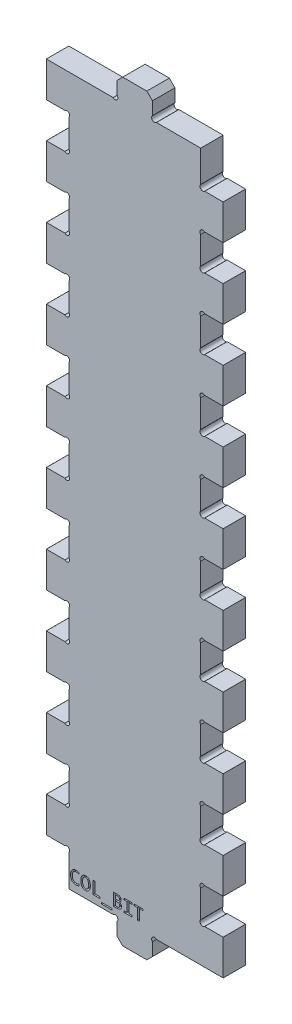
SolidWorks part; units mm, degrees
material "PVC Rigid"
ref_plane "Front Plane" through (0, 0, 0) normal (0, 0, 1) x (1, 0, 0)
ref_plane "Top Plane" through (0, 0, 0) normal (0, 1, 0) x (1, 0, 0)
ref_plane "Right Plane" through (0, 0, 0) normal (1, 0, 0) x (0, 0, -1)
sketch "Model" [suppressed]
  dimension "D3" = 0.7937
  dimension "D1" = 10
  dimension "D2" = 10
sketch "Sketch1" plane through (0, 0, 0) normal (0, 0, 1) x (1, 0, 0)
  line L1 (0, 0) -> (50, 0)
  line L2 (0, 0) -> (0, 200.0001)
  line L3 (0, 200.0001) -> (50, 200.0001)
  line L4 (50, 0) -> (50, 200.0001)
  dimension "D1" = 200.0001
  dimension "D2" = 50
extrude "Boss-Extrude1" add sketch "Sketch1" along normal blind 6.35
sketch "Sketch2" plane through (0, 0, 0) normal (0, 0, 1) x (1, 0, 0)
  line L0 (0, 100.0001) -> (50, 100.0001) construction
  line L1 (50, 200.0001) -> (0, 200.0001) construction
  line L2 (25, 200.0001) -> (25, 203.1751) construction
  line L3 (20, 206.3501) -> (30, 206.3501)
  line L4 (20, 206.3501) -> (20, 200.0001)
  line L5 (20, 200.0001) -> (30, 200.0001)
  line L6 (30, 206.3501) -> (30, 200.0001)
  line L7 (20, 206.3501) -> (30, 200.0001) construction
  line L8 (20, 200.0001) -> (30, 206.3501) construction
  line L9 (0, 200.0001) -> (0, 0) construction
  line L10 (50, 0) -> (50, 200.0001) construction
  line L11 (20, 0) -> (30, -6.35) construction
  line L12 (20, -6.35) -> (30, 0) construction
  line L13 (25, 0) -> (25, -3.175) construction
  line L14 (30, -6.35) -> (30, 0)
  line L15 (20, 0) -> (30, 0)
  line L16 (20, -6.35) -> (20, 0)
  line L17 (20, -6.35) -> (30, -6.35)
  dimension "D1" = 6.35
  dimension "D2" = 10
extrude "Boss-Extrude2" add sketch "Sketch2" along normal blind 6.35
sketch "Sketch3" plane through (0, 0, 6.35) normal (0, 0, 1) x (1, 0, 0)
  line L0 (25, 206.3501) -> (25, -6.35) construction
  line L1 (30, 206.3501) -> (20, 206.3501) construction
  line L2 (20, -6.35) -> (30, -6.35) construction
  line L3 (6.35, 200.0001) -> (6.35, 0) construction
  line L4 (20, 200.0001) -> (0, 200.0001) construction
  line L5 (0, 0) -> (20, 0) construction
  line L6 (0, 200.0001) -> (0, 0) construction
  line L7 (6.35, 0) -> (0, 0)
  line L8 (6.35, 0) -> (6.35, 10)
  line L9 (6.35, 10) -> (0, 10)
  line L10 (0, 0) -> (0, 10)
  line L11 (50, 0) -> (50, 10)
  line L12 (43.65, 10) -> (50, 10)
  line L13 (43.65, 0) -> (43.65, 10)
  line L14 (43.65, 0) -> (50, 0)
  dimension "D1" = 6.35
  dimension "D2" = 10
extrude "Cut-Extrude1" [suppressed] cut sketch "Sketch3" against normal blind 6.35
pattern_linear "LPattern2" [suppressed] count 10 spacing 20
sketch "Sketch4" [suppressed] plane through (0, 0, 6.35) normal (0, 0, 1) x (1, 0, 0)
  line L0 (0, 10) -> (6.35, 0) construction
  line L1 (6.35, 10) -> (5.2275, 10) construction
  line L2 (0.5613, 0.5613) -> (5.7887, 0.5613) construction
  line L3 (0.5613, 0.5613) -> (0.5613, 9.4387) construction
  line L4 (0.5613, 9.4387) -> (5.7887, 9.4387) construction
  line L5 (5.7887, 0.5613) -> (5.7887, 9.4387) construction
  line L6 (0.5613, 0.5613) -> (5.7887, 9.4387) construction
  line L7 (0.5613, 9.4387) -> (5.7887, 0.5613) construction
  line L8 (6.35, 10) -> (0, 10) construction
  line L9 (6.35, 10) -> (6.35, 8.8775) construction
  line L10 (6.35, 0) -> (6.35, 10) construction
  line L11 (25, 206.3501) -> (25, -6.35) construction
  line L12 (30, 206.3501) -> (20, 206.3501) construction
  line L13 (20, -6.35) -> (30, -6.35) construction
  line L14 (44.2113, 9.4387) -> (44.2113, 20.5613) construction
  line L15 (43.65, 10) -> (43.65, 8.8775) construction
  line L16 (49.4387, 9.4387) -> (44.2113, 0.5613) construction
  line L17 (49.4387, 0.5613) -> (44.2113, 9.4387) construction
  line L18 (44.2113, 0.5613) -> (44.2113, 9.4387) construction
  line L19 (49.4387, 9.4387) -> (44.2113, 9.4387) construction
  line L20 (49.4387, 0.5613) -> (49.4387, 9.4387) construction
  line L21 (49.4387, 0.5613) -> (44.2113, 0.5613) construction
  line L22 (43.65, 10) -> (44.7725, 10) construction
  line L23 (5.7887, 9.4387) -> (5.7887, 20.5613) construction
  line L24 (50, 10) -> (43.65, 0) construction
  circle A0 centre (5.7887, 9.4387) radius 0.7938
  circle A4 centre (5.7887, 20.5613) radius 0.7938
  circle A7 centre (44.2113, 20.5613) radius 0.7937
  circle A8 centre (44.2113, 9.4387) radius 0.7937
  point P4 (3.175, 5)
  point P40 (46.825, 5)
  dimension "D1" = 1.5875
extrude "Cut-Extrude3" [suppressed] cut sketch "Sketch4" against normal blind 6.35
pattern_linear "LPattern3" [suppressed] count 9 spacing 20
sketch "Sketch8" plane through (0, 0, 6.35) normal (0, 0, 1) x (1, 0, 0)
  line L0 (6.35, 200.0001) -> (6.35, 0) construction
  line L1 (20, 200.0001) -> (0, 200.0001) construction
  line L2 (0, 0) -> (20, 0) construction
  line L3 (0, 200.0001) -> (0, 0) construction
  line L4 (43.65, 200.0001) -> (43.65, 0) construction
  line L5 (0, 0) -> (6.35, 0)
  line L6 (0, 0) -> (0, 10)
  line L7 (0, 10) -> (6.35, 10)
  line L8 (6.35, 0) -> (6.35, 10)
  line L9 (50, 200.0001) -> (30, 200.0001) construction
  line L10 (30, 0) -> (50, 0) construction
  line L11 (50, 0) -> (50, 200.0001) construction
  line L12 (43.65, 10) -> (50, 10)
  line L13 (43.65, 10) -> (43.65, 20)
  line L14 (43.65, 20) -> (50, 20)
  line L15 (50, 10) -> (50, 20)
  dimension "D1" = 6.35
  dimension "D2" = 10
  dimension "D3" = 10
  dimension "D4" = 6.35
  dimension "D5" = 10
extrude "Cut-Extrude6" cut sketch "Sketch8" against normal through all
pattern_linear "LPattern4" count 10 spacing 20 along (0, 1, 0) of "Cut-Extrude6"
sketch "Sketch9" plane through (0, 0, 6.35) normal (0, 0, 1) x (1, 0, 0)
  line L0 (0, 30) -> (6.35, 20) construction
  line L1 (6.35, 30) -> (5.2275, 30) construction
  line L2 (0.5613, 20.5613) -> (5.7887, 20.5613) construction
  line L3 (0.5613, 20.5613) -> (0.5613, 29.4388) construction
  line L4 (0.5613, 29.4388) -> (5.7887, 29.4388) construction
  line L5 (5.7887, 20.5613) -> (5.7887, 29.4388) construction
  line L6 (0.5613, 20.5613) -> (5.7887, 29.4388) construction
  line L7 (0.5613, 29.4388) -> (5.7887, 20.5613) construction
  line L8 (6.35, 30) -> (0, 30) construction
  line L9 (6.35, 30) -> (6.35, 28.8775) construction
  line L10 (6.35, 20) -> (6.35, 30) construction
  line L11 (43.65, 20) -> (50, 10) construction
  line L12 (43.65, 20) -> (44.7725, 20) construction
  line L13 (44.2113, 10.5613) -> (49.4387, 10.5613) construction
  line L14 (44.2113, 10.5613) -> (44.2113, 19.4387) construction
  line L15 (44.2113, 19.4387) -> (49.4387, 19.4387) construction
  line L16 (49.4387, 10.5613) -> (49.4387, 19.4387) construction
  line L17 (44.2113, 10.5613) -> (49.4387, 19.4387) construction
  line L18 (44.2113, 19.4387) -> (49.4387, 10.5613) construction
  line L19 (50, 20) -> (43.65, 20) construction
  line L20 (43.65, 20) -> (43.65, 18.8775) construction
  line L21 (43.65, 20) -> (43.65, 10) construction
  line L22 (50, 20) -> (50, 30) construction
  circle A0 centre (5.7887, 29.4388) radius 0.7938
  circle A1 centre (5.7887, 20.5613) radius 0.7938
  circle A2 centre (44.2113, 19.4387) radius 0.7937
  circle A3 centre (44.2113, 10.5613) radius 0.7937
  point P4 (3.175, 25)
  point P23 (46.825, 15)
  dimension "D1" = 1.5875
  dimension "D2" = 10
extrude "Cut-Extrude7" cut sketch "Sketch9" against normal through all
pattern_linear "LPattern5" count 9 spacing 20 along (0, 1, 0) of "Cut-Extrude7"
sketch "Sketch10" plane through (0, 0, 6.35) normal (0, 0, 1) x (1, 0, 0)
  line L0 (0, 10) -> (6.35, 0) construction
  line L1 (5.2275, 10) -> (6.35, 10) construction
  line L2 (0.5613, 0.5613) -> (5.7887, 0.5613) construction
  line L3 (0.5613, 0.5613) -> (0.5613, 9.4387) construction
  line L4 (0.5613, 9.4387) -> (5.7887, 9.4387) construction
  line L5 (5.7887, 0.5613) -> (5.7887, 9.4387) construction
  line L6 (0.5613, 0.5613) -> (5.7887, 9.4387) construction
  line L7 (0.5613, 9.4387) -> (5.7887, 0.5613) construction
  line L8 (6.35, 10) -> (0, 10) construction
  line L9 (6.35, 10) -> (6.35, 8.8775) construction
  line L10 (6.35, 0) -> (6.35, 10) construction
  line L11 (6.35, 5) -> (3.175, 5) construction
  line L12 (0, 200.0001) -> (50, 0) construction
  line L13 (43.65, 200.0001) -> (50, 190.0001) construction
  line L14 (44.7725, 190.0001) -> (43.65, 190.0001) construction
  line L15 (44.2113, 190.5614) -> (49.4387, 190.5614) construction
  line L16 (44.2113, 190.5614) -> (44.2113, 199.4388) construction
  line L17 (44.2113, 199.4388) -> (49.4387, 199.4388) construction
  line L18 (49.4387, 190.5614) -> (49.4387, 199.4388) construction
  line L19 (44.2113, 190.5614) -> (49.4387, 199.4388) construction
  line L20 (44.2113, 199.4388) -> (49.4387, 190.5614) construction
  line L21 (43.65, 190.0001) -> (50, 190.0001) construction
  line L22 (43.65, 190.0001) -> (43.65, 191.1226) construction
  line L23 (43.65, 200.0001) -> (43.65, 190.0001) construction
  circle A0 centre (5.7887, 9.4387) radius 0.7938
  circle A2 centre (44.2113, 190.5614) radius 0.7937
  point P4 (3.175, 5)
  point P28 (46.825, 195.0001)
  dimension "D1" = 1.5875
  dimension "D2" = 1.5875
extrude "Cut-Extrude8" cut sketch "Sketch10" against normal through all
chamfer "Chamfer1" distance 1.5875 angle 45 4 edges at (30, -6.35, 3.175) (20, -6.35, 3.175) (20, 206.3501, 3.175) (30, 206.3501, 3.175)
sketch "Sketch5" [suppressed] plane through (0, 0, 6.35) normal (0, 0, 1) x (1, 0, 0)
  line L0 (6.35, 180.0001) -> (0, 190.0001) construction
  line L1 (6.35, 190.0001) -> (5.2275, 190.0001) construction
  line L2 (0.5613, 180.5614) -> (5.7887, 180.5614) construction
  line L3 (0.5613, 180.5614) -> (0.5613, 189.4388) construction
  line L4 (0.5613, 189.4388) -> (5.7887, 189.4388) construction
  line L5 (5.7887, 180.5614) -> (5.7887, 189.4388) construction
  line L6 (0.5613, 180.5614) -> (5.7887, 189.4388) construction
  line L7 (0.5613, 189.4388) -> (5.7887, 180.5614) construction
  line L8 (6.35, 190.0001) -> (0, 190.0001) construction
  line L9 (6.35, 190.0001) -> (6.35, 188.8776) construction
  line L10 (6.35, 181.1226) -> (6.35, 190.0001) construction
  line L15 (25, 206.3501) -> (25, -6.35) construction
  line L16 (28.4125, 206.3501) -> (21.5875, 206.3501) construction
  line L17 (21.5875, -6.35) -> (28.4125, -6.35) construction
  line L20 (43.65, 190.0001) -> (43.65, 188.8776) construction
  line L21 (49.4387, 189.4388) -> (44.2113, 180.5614) construction
  line L22 (49.4387, 180.5614) -> (44.2113, 189.4388) construction
  line L23 (44.2113, 180.5614) -> (44.2113, 189.4388) construction
  line L24 (49.4387, 189.4388) -> (44.2113, 189.4388) construction
  line L25 (49.4387, 180.5614) -> (49.4387, 189.4388) construction
  line L26 (49.4387, 180.5614) -> (44.2113, 180.5614) construction
  line L27 (43.65, 190.0001) -> (44.7725, 190.0001) construction
  line L28 (43.65, 180.0001) -> (50, 190.0001) construction
  line L29 (50, 100.0001) -> (0, 100.0001) construction
  arc A0 (5.2275, 180.0001) -> (6.35, 181.1226) centre (5.7887, 180.5614) ccw construction
  circle A1 centre (5.7887, 189.4388) radius 0.7938
  circle A4 centre (44.2113, 189.4388) radius 0.7937
  point P6 (3.175, 185.0001)
  point P51 (46.825, 185.0001)
  point P56 (25, 100.0001)
  dimension "D1" = 1.5875
extrude "Cut-Extrude4" [suppressed] cut sketch "Sketch5" against normal blind 6.35
sketch "Sketch11" plane through (0, 0, 0) normal (0, 0, 1) x (1, 0, 0)
  line L0 (28.4125, 206.3501) -> (21.5875, 206.3501) construction
  line L11 (20, 201.1226) -> (20, 200.0001) construction
  line L13 (20, 200.0001) -> (18.8775, 200.0001) construction
  line L15 (25, 206.3501) -> (25, -6.35) construction
  line L18 (30, 200.0001) -> (31.1225, 200.0001) construction
  line L19 (30, 201.1226) -> (30, 200.0001) construction
  line L29 (50, 100.0001) -> (0, 100.0001) construction
  circle A2 centre (19.4387, 200.5614) radius 0.7937
  circle A3 centre (30.5613, 200.5614) radius 0.7937
  circle A5 centre (19.4387, -0.5613) radius 0.7937
  circle A6 centre (30.5613, -0.5613) radius 0.7937
  point P56 (25, 100.0001)
  dimension "D1" = 1.5875
  dimension "D2" = 19.4387
  dimension "D3" = 100.0001
  dimension "D4" = 200.0001
extrude "Cut-Extrude10" cut sketch "Sketch11" along normal through all
sketch "Sketch6" [suppressed] plane through (0, 0, 6.35) normal (0, 0, 1) x (1, 0, 0)
  line L0 (6.604, 2.032) -> (43.65, 2.032) construction
  line L1 (43.65, 10) -> (43.65, 0) construction
  line L2 (6.35, 0) -> (18.8775, 0) construction
  line L4 (0, 20) -> (0, 10) construction
  text T0 "COL_BIT" font "Consolas" height 3.5
  dimension "D1" = 2.032
  dimension "D2" = 6.604
extrude "Cut-Extrude5" [suppressed] cut sketch "Sketch6" against normal blind 2.54
sketch "Sketch12" plane through (0, 0, 6.35) normal (0, 0, 1) x (1, 0, 0)
  line L0 (6.604, 2.032) -> (40.0372, 2.032) construction
  text T0 "COL_BIT" font "Consolas" height 3.5
  dimension "D1" = 2.032
  dimension "D2" = 6.604
extrude "Cut-Extrude11" cut sketch "Sketch12" against normal blind 2.54
sketch "Sketch13" [suppressed] plane through (0, 0, 6.35) normal (0, 0, 1) x (1, 0, 0)
  line L0 (0, 10) -> (6.35, 0) construction
  line L1 (5.2275, 10) -> (0, 10) construction
  line L2 (6.337, -0.0127) -> (0.013, -0.0127)
  line L3 (6.337, -0.0127) -> (6.337, 10.0127)
  line L4 (6.337, 10.0127) -> (0.013, 10.0127)
  line L5 (0.013, -0.0127) -> (0.013, 10.0127)
  line L6 (6.337, -0.0127) -> (0.013, 10.0127) construction
  line L7 (6.337, 10.0127) -> (0.013, -0.0127) construction
  line L8 (25, 206.3501) -> (25, -6.35) construction
  line L9 (28.4125, 206.3501) -> (21.5875, 206.3501) construction
  line L10 (21.5875, -6.35) -> (28.4125, -6.35) construction
  line L11 (43.663, 10.0127) -> (49.987, -0.0127) construction
  line L12 (43.663, -0.0127) -> (49.987, 10.0127) construction
  line L13 (50, 10) -> (43.65, 0) construction
  line L14 (49.987, -0.0127) -> (49.987, 10.0127)
  line L15 (43.663, 10.0127) -> (49.987, 10.0127)
  line L16 (43.663, -0.0127) -> (43.663, 10.0127)
  line L17 (43.663, -0.0127) -> (49.987, -0.0127)
  arc A0 (6.35, 8.8775) -> (5.2275, 10) centre (5.7887, 9.4387) ccw construction
  point P4 (3.175, 5)
  point P26 (46.825, 5)
  dimension "D1" = 0.0127
extrude "Cut-Extrude12" [suppressed] cut sketch "Sketch13" against normal through all
pattern_linear "LPattern6" [suppressed] count 10 spacing 20
sketch "Sketch14" plane through (0, 0, 6.35) normal (0, 0, 1) x (1, 0, 0)
  line L0 (0, 10) -> (6.35, 0) construction
  line L1 (5.2275, 10) -> (0, 10) construction
  line L2 (0.013, -0.0127) -> (6.337, -0.0127)
  line L3 (0.013, -0.0127) -> (0.013, 10.0127)
  line L4 (0.013, 10.0127) -> (6.337, 10.0127)
  line L5 (6.337, -0.0127) -> (6.337, 10.0127)
  line L6 (0.013, -0.0127) -> (6.337, 10.0127) construction
  line L7 (0.013, 10.0127) -> (6.337, -0.0127) construction
  line L8 (43.65, 20) -> (50, 10) construction
  line L9 (50, 20) -> (44.7725, 20) construction
  line L10 (43.663, 9.9873) -> (49.987, 9.9873)
  line L11 (43.663, 9.9873) -> (43.663, 20.0127)
  line L12 (43.663, 20.0127) -> (49.987, 20.0127)
  line L13 (49.987, 9.9873) -> (49.987, 20.0127)
  line L14 (43.663, 9.9873) -> (49.987, 20.0127) construction
  line L15 (43.663, 20.0127) -> (49.987, 9.9873) construction
  arc A0 (6.35, 8.8775) -> (5.2275, 10) centre (5.7887, 9.4387) ccw construction
  arc A1 (44.7725, 20) -> (43.65, 18.8775) centre (44.2113, 19.4387) ccw construction
  point P4 (3.175, 5)
  point P9 (46.825, 15)
  dimension "D1" = 0.0127
  dimension "D2" = 0.0127
extrude "Cut-Extrude13" cut sketch "Sketch14" against normal through all
pattern_linear "LPattern7" count 10 spacing 20 along (0, 1, 0) of "Cut-Extrude13"
equation "\"tHeight\"=0.25"
equation "\"D1@Sketch2\"=\"tHeight\""
equation "\"tWidth\"=0.393701"
equation "\"D2@Sketch2\"=\"tWidth\""
equation "\"D1@Sketch1\"=\"tWidth\"*20"
equation "\"D1@Sketch3\"=\"tHeight\""
equation "\"D2@Sketch3\"=\"tWidth\""
equation "\"D3@LPattern1\"=\"tWidth\"*2"
equation "\"D3@LPattern2\"=\"tWidth\"*2"
equation "\"D3@LPattern3\"=\"tWidth\"*2"
equation "\"D1@Sketch8\"=\"tHeight\""
equation "\"D2@Sketch8\"=\"tWidth\""
equation "\"D3@Sketch8\"=\"tWidth\""
equation "\"D4@Sketch8\"=\"tHeight\""
equation "\"D5@Sketch8\"=\"tWidth\""
equation "\"D3@LPattern4\"=\"tWidth\"*2"
equation "\"D3@LPattern5\"=\"tWidth\"*2"
equation "\"D2@Sketch9\"=\"tWidth\""
equation "\"tol\"=0.0005"
equation "\"D1@Sketch13\"=\"tol\""
equation "\"D3@LPattern6\"=\"tWidth\"*2"
equation "\"D1@Sketch14\"=\"tol\""
equation "\"D2@Sketch14\"=\"tol\""
